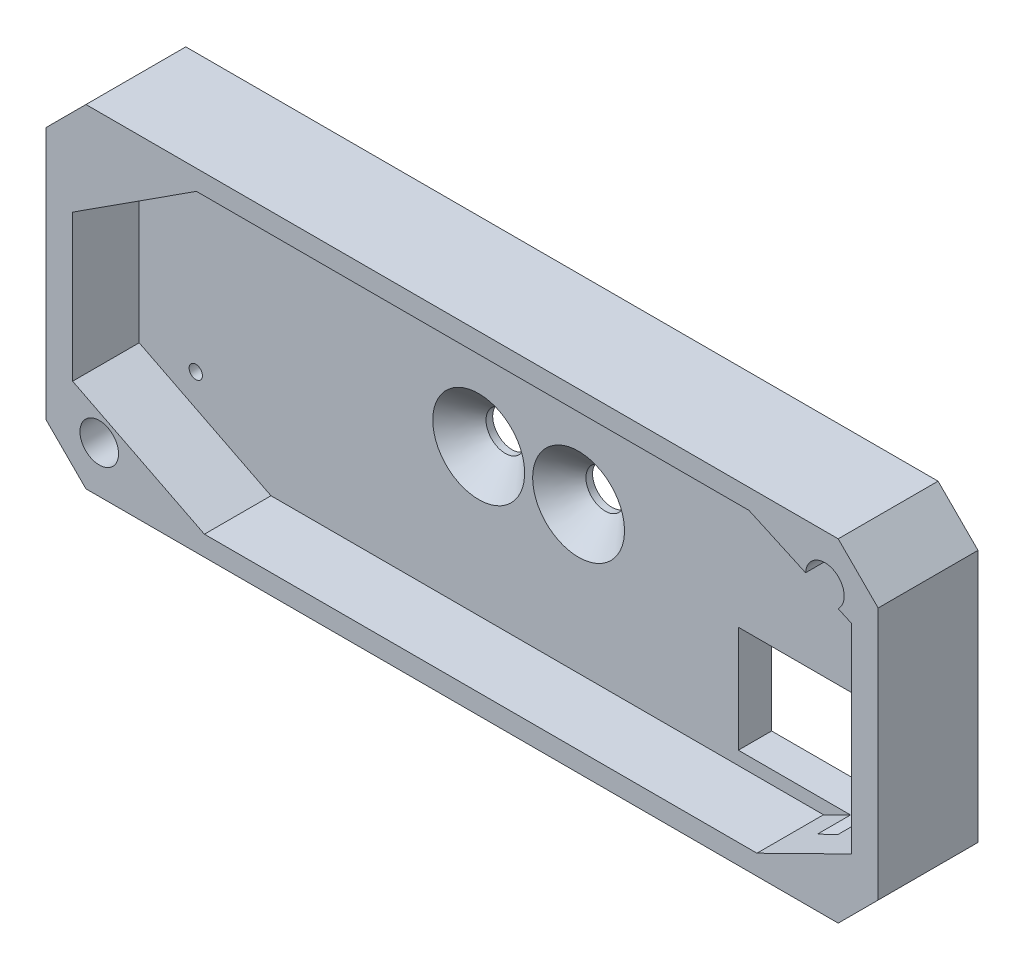
SolidWorks part; units mm, degrees
ref_plane "Спереди" through (0, 0, 0) normal (0, 0, 1) x (1, 0, 0)
ref_plane "Сверху" through (0, 0, 0) normal (0, 1, 0) x (1, 0, 0)
ref_plane "Справа" through (0, 0, 0) normal (1, 0, 0) x (0, 0, -1)
sketch "Эскиз1" plane through (0, 0, 0) normal (0, 0, 1) x (1, 0, 0)
  line L1 (-31.25, -12.5) -> (31.25, -12.5)
  line L2 (-31.25, -12.5) -> (-31.25, 12.5)
  line L3 (-31.25, 12.5) -> (31.25, 12.5)
  line L4 (31.25, -12.5) -> (31.25, 12.5)
  line L5 (-31.25, -12.5) -> (31.25, 12.5) construction
  line L6 (-31.25, 12.5) -> (31.25, -12.5) construction
  point P0 (0, 0)
  dimension "D1" = 25
  dimension "D2" = 62.5
extrude "Бобышка-Вытянуть1" add sketch "Эскиз1" along normal blind 2.5
sketch "Эскиз2" plane through (0, 0, 2.5) normal (0, 0, 1) x (1, 0, 0)
  line L0 (0, 0) -> (50000, 0) construction
  circle A0 centre (3.75, 0) radius 1.45
  circle A1 centre (-3.75, 0) radius 1.45
  dimension "D3" = 2.9
  dimension "D1" = 7.5
  dimension "D2" = 3.75
extrude "Вырез-Вытянуть1" cut sketch "Эскиз2" against normal blind 3.5
chamfer "Фаска1" distance 2 angle 45 2 edges at (-2.3, 0, 2.5) (5.2, 0, 2.5)
sketch "Эскиз3" plane through (0, 0, 2.5) normal (0, 0, 1) x (1, 0, 0)
  line L0 (-29.25, -6) -> (-29.25, 5)
  line L1 (-29.25, 5) -> (-19.95, 11)
  line L2 (-19.95, 11) -> (21.55, 11)
  line L3 (21.55, 11) -> (29.25, 7.5)
  line L4 (29.25, 7.5) -> (29.25, -7.5)
  line L5 (29.25, -7.5) -> (22.148, -11)
  line L6 (22.148, -11) -> (-19.352, -11)
  line L7 (-19.352, -11) -> (-29.25, -6)
  line L8 (-31.25, 12.5) -> (-31.25, -12.5) construction
  line L9 (31.25, 12.5) -> (-31.25, 12.5) construction
  line L10 (-31.25, -12.5) -> (31.25, -12.5) construction
  line L11 (31.25, -12.5) -> (31.25, 12.5) construction
  line L13 (-31.25, 12.5) -> (31.25, 12.5)
  line L14 (-31.25, 12.5) -> (-31.25, -12.5)
  line L15 (-31.25, -12.5) -> (31.25, -12.5)
  line L16 (31.25, 12.5) -> (31.25, -12.5)
  point P8 (-29.25, -0.5)
  point P9 (1.398, -11)
  dimension "D2" = 1.5
  dimension "D3" = 2
  dimension "D4" = 11
  dimension "D5" = 6
  dimension "D6" = 3.5
  dimension "D7" = 15
  dimension "D8" = 9.3
  dimension "D9" = 41.5
  dimension "D10" = 9.898
  dimension "D11" = 2
  dimension "D12" = 1.5
  dimension "D13" = 41.5
extrude "Бобышка-Вытянуть2" add sketch "Эскиз3" along normal blind 5
sketch "Эскиз4" plane through (0, 0, 0) normal (0, 0, -1) x (-1, 0, 0)
  line L0 (31.25, -12.5) -> (-31.25, -12.5) construction
  line L1 (-15.75, -2) -> (-25.75, -2)
  line L2 (-15.75, -2) -> (-15.75, -10)
  line L3 (-15.75, -10) -> (-25.75, -10)
  line L4 (-25.75, -2) -> (-25.75, -10)
  line L5 (-31.25, -12.5) -> (-31.25, 12.5) construction
  dimension "D1" = 2.5
  dimension "D2" = 8
  dimension "D3" = 10
  dimension "D4" = 5.5
extrude "Вырез-Вытянуть2" cut sketch "Эскиз4" against normal blind 5
sketch "Эскиз5" plane through (0, 0, 7.5) normal (0, 0, 1) x (1, 0, 0)
  line L0 (-28.25, 12.5) -> (-31.25, 9.5)
  line L1 (-31.25, -9.5) -> (-28.25, -12.5)
  line L2 (28.25, -12.5) -> (31.25, -9.5)
  line L3 (31.25, 9.5) -> (28.25, 12.5)
  line L4 (-31.25, 12.5) -> (-31.25, -12.5)
  line L5 (-31.25, -12.5) -> (31.25, -12.5)
  line L6 (31.25, -12.5) -> (31.25, 12.5)
  line L7 (31.25, 12.5) -> (-31.25, 12.5)
  line L8 (-31.25, 9.5) -> (-31.25, -9.5)
  line L9 (-28.25, -12.5) -> (28.25, -12.5)
  line L10 (31.25, -9.5) -> (31.25, 9.5)
  line L11 (28.25, 12.5) -> (-28.25, 12.5)
  line L13 (-33.317, 15.2838) -> (34.2491, 15.2838)
  line L14 (-33.317, 15.2838) -> (-33.317, -14.7046)
  line L15 (-33.317, -14.7046) -> (34.2491, -14.7046)
  line L16 (34.2491, 15.2838) -> (34.2491, -14.7046)
  dimension "D2" = 3
  dimension "D3" = 45
  dimension "D4" = 3
  dimension "D5" = 45
  dimension "D6" = 3
  dimension "D7" = 45
  dimension "D8" = 3
  dimension "D9" = 45
  dimension "D1" = 0
extrude "Вырез-Вытянуть3" cut sketch "Эскиз5" against normal blind 10
sketch "Эскиз7" plane through (0, 0, 7.5) normal (0, 0, 1) x (1, 0, 0)
  line L0 (-31.25, 9.5) -> (-31.25, -9.5) construction
  line L1 (-28.25, -12.5) -> (28.25, -12.5) construction
  line L2 (28.25, 12.5) -> (-28.25, 12.5) construction
  line L3 (31.25, -9.5) -> (31.25, 9.5) construction
  circle A1 centre (-27.25, -9) radius 1.45
  circle A2 centre (27.25, 9) radius 1.45
  dimension "D1" = 2.9
  dimension "D2" = 4
  dimension "D3" = 3.5
  dimension "D4" = 3.5
  dimension "D5" = 4
extrude "Вырез-Вытянуть4" cut sketch "Эскиз7" against normal blind 10
sketch "Эскиз10" plane through (0, 0, 2.5) normal (0, 0, 1) x (1, 0, 0)
  line L0 (29.25, -7.5) -> (29.25, 7.5) construction
  line L1 (21.55, 11) -> (-19.95, 11) construction
  line L3 (-29.25, 5) -> (-29.25, -6) construction
  line L4 (-19.352, -11) -> (22.148, -11) construction
  circle A0 centre (-25, -5.7661) radius 0.5
  circle A1 centre (26.548, 6) radius 0.5
  dimension "D3" = 1
  dimension "D6" = 1
  dimension "D1" = 2.702
  dimension "D2" = 5
  dimension "D4" = 4.25
  dimension "D5" = 5.2339
extrude "Вырез-Вытянуть5" cut sketch "Эскиз10" against normal blind 10
